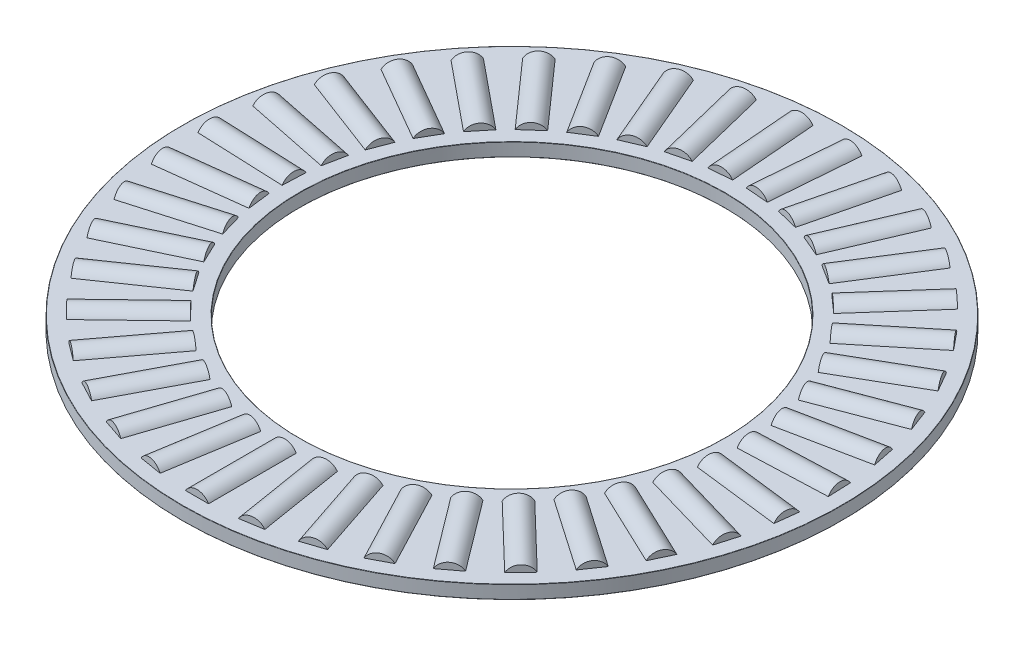
SolidWorks part; units mm, degrees
ref_plane "Front Plane" through (0, 0, 0) normal (0, 0, 1) x (1, 0, 0)
ref_plane "Top Plane" through (0, 0, 0) normal (0, 1, 0) x (1, 0, 0)
ref_plane "Right Plane" through (0, 0, 0) normal (1, 0, 0) x (0, 0, -1)
sketch "Sketch1" plane through (0, 0, 0) normal (1, 0, 0) x (0, 0, -1)
  line L0 (-24.6062, 0) -> (24.6062, 0) construction
  line L1 (0, -0.9922) -> (0, 0.9922) construction
  line L2 (-24.6062, 0.4961) -> (-15.875, 0.4961)
  line L3 (-24.6062, 0.4961) -> (-24.6062, -0.4961)
  line L4 (-24.6062, -0.4961) -> (-15.875, -0.4961)
  line L5 (-15.875, 0.4961) -> (-15.875, -0.4961)
  line L7 (-20.2406, 0.9922) -> (-20.2406, 0.4961) construction
  line L8 (-23.5148, 0.9922) -> (-16.9664, 0.9922) construction
  line L9 (-23.5148, 0.9922) -> (-23.5148, -0.9922) construction
  line L10 (-23.5148, -0.9922) -> (-16.9664, -0.9922) construction
  line L11 (-16.9664, 0.9922) -> (-16.9664, -0.9922) construction
  point P16 (-23.5148, 0)
  dimension "OD" = 49.2125
  dimension "Shaft Dia" = 31.75
  dimension "Th" = 1.9844
  dimension "D2" = 0.9922
  dimension "D1" = 6.5484
  dimension "D3" = 8.7312
revolve "Revolve1" add sketch "Sketch1" angle 360 about L1
sketch "Sketch3" plane through (0, 0, 0) normal (1, 0, 0) x (0, 0, -1)
  line L0 (-23.5148, 0.9922) -> (-23.5148, -0.9922) construction
  line L1 (-23.5148, 0) -> (-16.9664, 0)
  line L2 (-23.5148, 0) -> (-23.5148, 0.9922)
  line L3 (-23.5148, 0.9922) -> (-16.9664, 0.9922)
  line L4 (-16.9664, 0) -> (-16.9664, 0.9922)
revolve "Cut-Revolve1" cut sketch "Sketch3" angle 360 about L1
sketch "Sketch2" plane through (0, 0, 0) normal (1, 0, 0) x (0, 0, -1)
  line L1 (-23.5148, 0) -> (-16.9664, 0)
  line L2 (-23.5148, 0) -> (-23.5148, 0.9922)
  line L3 (-23.5148, 0.9922) -> (-16.9664, 0.9922)
  line L4 (-16.9664, 0) -> (-16.9664, 0.9922)
revolve "Revolve2" add sketch "Sketch2" angle 360 about L1
ref_axis "Axis1" through (0, 0.9922, 0) along (0, -1, 0)
pattern_circular "CirPattern1" count 39 every 9.231 about axis through (0, 0.9922, 0) along (0, -1, 0) of bodies 187 411
pattern_circular "CirPattern2" count 39 every 9.231 about axis through (0, 0, 0) along (0, 1, 0) of "Cut-Revolve1"
sketch "Sketch4" plane through (0, 0, 0) normal (1, 0, 0) x (0, 0, -1)
  line L0 (-24.6062, 0.4961) -> (-24.6062, -0.4961) construction
  line L1 (-24.6062, 9.1091) -> (-15.875, 9.1091)
  line L2 (-24.6062, 9.1091) -> (-24.6063, 9.9219)
  line L3 (-24.6063, 9.9219) -> (-15.875, 9.9219)
  line L4 (-15.875, 9.1091) -> (-15.875, 9.9219)
  line L5 (-24.6062, -9.9219) -> (-15.875, -9.9219)
  line L6 (-24.6062, -9.9219) -> (-24.6062, -9.1091)
  line L7 (-24.6062, -9.1091) -> (-15.875, -9.1091)
  line L8 (-15.875, -9.9219) -> (-15.875, -9.1091)
  line L10 (-15.875, 0.4961) -> (-15.875, -0.4961) construction
  line L11 (0, 0) -> (-24.6062, 0) construction
  line L12 (-24.6062, 0) -> (24.6062, 0) construction
  line L13 (0, -0.9922) -> (0, 0.9922) construction
  dimension "Ht" = 19.8438
  dimension "Washer Th" = 0.8128
  dimension "Washer ID" = 31.75
  dimension "Washer OD" = 49.2125
revolve "Revolve3" [suppressed] add sketch "Sketch4" angle 360 about L1
fillet "Fillet1" [suppressed] radius 0.0198
fillet "Fillet2" radius 0.0198 4 edges at (0, -0.4961, -15.875) (0, 0.4961, -15.875) (0, -0.4961, -24.6062) (0, 0.4961, -24.6062)
fillet "Fillet3" [suppressed] radius 0.0198
equation "\"D2@Sketch1\" = \"Th@Sketch1\"*.5"
equation "\"D1@Fillet1\" = \"Th@Sketch1\"*.01"
equation "\"D1@Fillet2\" = \"D1@Fillet1\""
equation "\"D1@Fillet3\" = \"D1@Fillet1\""
equation "\"D1@Sketch1\" = \"D3@Sketch1\"*.75"
equation "\"Angle@CirPattern1\" = 360/\"Rollers@CirPattern1\""
equation "\"Rollers@CirPattern1\" = \"OD@Sketch1\"*20"
equation "\"D1@CirPattern2\" = \"Rollers@CirPattern1\""
equation "\"D2@CirPattern2\" = \"Angle@CirPattern1\""
equation "\"Ht@Sketch4\" = \"Th@Sketch1\"*10"
